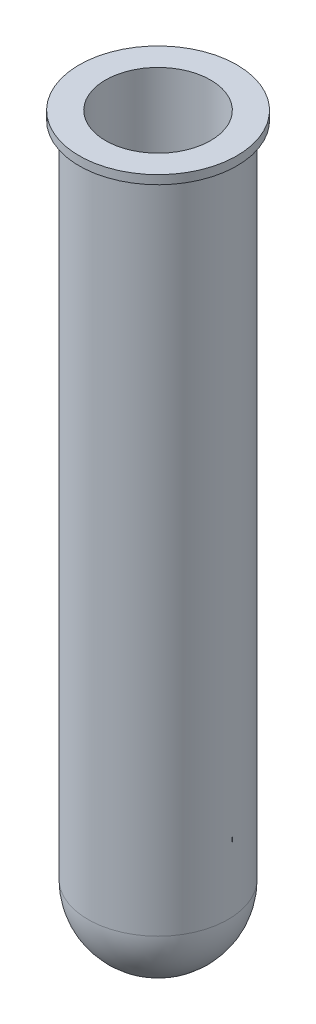
SolidWorks part; units mm, degrees
material "PP Film"
ref_plane "Front Plane" through (0, 0, 0) normal (0, 0, 1) x (1, 0, 0)
ref_plane "Top Plane" through (0, 0, 0) normal (0, 1, 0) x (1, 0, 0)
ref_plane "Right Plane" through (0, 0, 0) normal (1, 0, 0) x (0, 0, -1)
sketch "Sketch2" plane through (0, 0, 0) normal (0, 0, 1) x (1, 0, 0)
  line L0 (0, 0) -> (0, 6) construction
  line L1 (0, 6) -> (-6, 6) construction
  line L2 (-6, 6) -> (-6, 81)
  line L3 (-8, 6) -> (-8, 81)
  line L4 (-6, 81) -> (-6, 82)
  line L5 (-6, 82) -> (-9, 82)
  line L6 (-9, 82) -> (-9, 81)
  line L7 (-9, 81) -> (-8, 81)
  line L8 (0, 0) -> (0, -2)
  arc A0 (-8, 6) -> (0, -2) centre (0, 6) ccw
  arc A2 (-6, 6) -> (0, 0) centre (0, 6) ccw
  dimension "D3" = 2
  dimension "D1" = 6
  dimension "D2" = 75
  dimension "D4" = 3
  dimension "D5" = 1
revolve "Revolve1" add sketch "Sketch2" angle 360 about L0
ref_point "Point2"
ref_plane "Plane1" through (0, 82, 0) normal (0, 1, 0) x (1, 0, 0)
sketch "Sketch3" plane through (0, 82, 0) normal (0, 1, 0) x (1, 0, 0)
  line L0 (0, 0) -> (9, 0) construction
  line L1 (0, 0) -> (0, 9) construction
  circle A0 centre (0, 0) radius 9 construction
ref_plane "Plane2" through (0, 0, 0) normal (1, 0, 0) x (0, 0, -1)
sketch "Sketch4" plane through (0, 0, 0) normal (1, 0, 0) x (0, 0, -1)
  line L0 (0, 82) -> (0, 6) construction
  line L1 (8, 6) -> (-8, 6) construction
